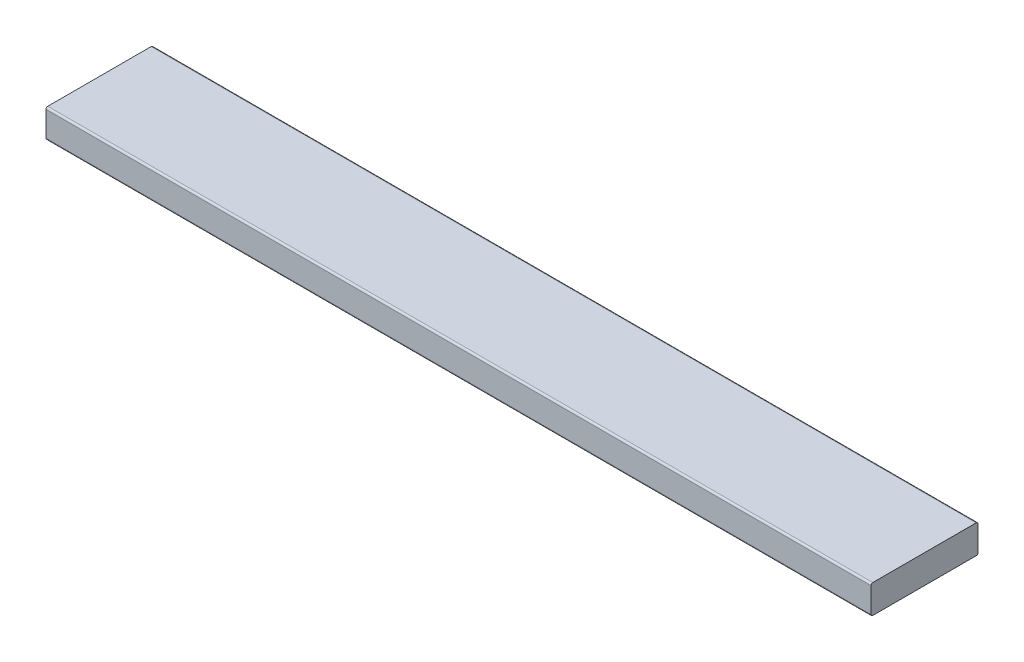
SolidWorks part; units mm, degrees
ref_plane "Front Plane" through (0, 0, 0) normal (0, 0, 1) x (1, 0, 0)
ref_plane "Top Plane" through (0, 0, 0) normal (0, 1, 0) x (1, 0, 0)
ref_plane "Right Plane" through (0, 0, 0) normal (1, 0, 0) x (0, 0, -1)
sketch "Sketch2" plane through (0, 0, 0) normal (1, 0, 0) x (0, 0, -1)
  line L1 (-60, -16) -> (60, -16)
  line L2 (-60, -16) -> (-60, 16)
  line L3 (-60, 16) -> (60, 16)
  line L4 (60, -16) -> (60, 16)
  line L5 (-60, -16) -> (60, 16) construction
  line L6 (-60, 16) -> (60, -16) construction
  point P0 (0, 0)
  dimension "D1" = 120
  dimension "D2" = 32
extrude "Boss-Extrude1" add sketch "Sketch2" along normal mid plane 925
fillet "Fillet1" radius 2 4 edges at (0, -16, -60) (0, 16, -60) (0, -16, 60) (0, 16, 60)
